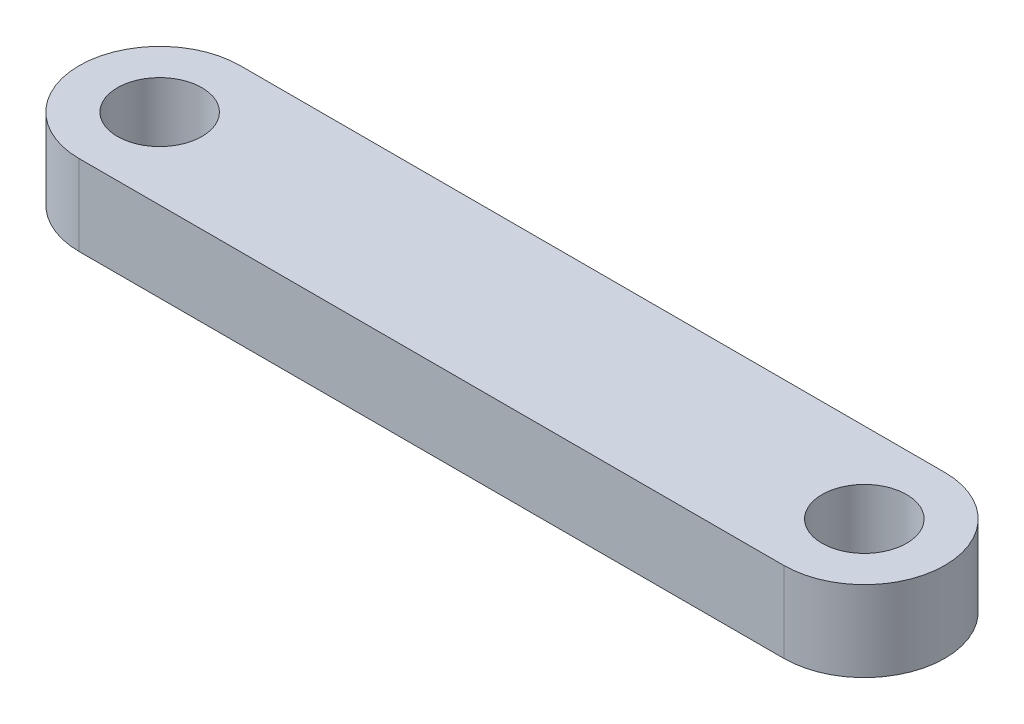
SolidWorks part; units mm, degrees
ref_plane "Front Plane" through (0, 0, 0) normal (0, 0, 1) x (1, 0, 0)
ref_plane "Top Plane" through (0, 0, 0) normal (0, 1, 0) x (1, 0, 0)
ref_plane "Right Plane" through (0, 0, 0) normal (1, 0, 0) x (0, 0, -1)
sketch "Sketch1" plane through (0, 0, 0) normal (0, 1, 0) x (1, 0, 0)
  line L0 (0, 0) -> (17.5, 0) construction
  line L1 (0, 2) -> (17.5, 2)
  line L2 (0, -2) -> (17.5, -2)
  arc A0 (0, 2) -> (0, -2) centre (0, 0) ccw
  arc A1 (17.5, -2) -> (17.5, 2) centre (17.5, 0) ccw
  circle A2 centre (0, 0) radius 1.05
  circle A3 centre (17.5, 0) radius 1.05
  point P3 (8.75, 0)
  dimension "D2" = 2
  dimension "D4" = 2.1
  dimension "D5" = 2.1
  dimension "D1" = 17.5
extrude "Boss-Extrude1" add sketch "Sketch1" along normal blind 2
